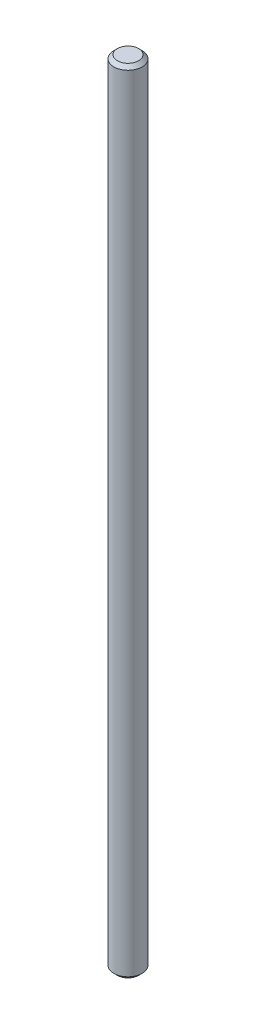
SolidWorks part; units mm, degrees
ref_plane "Front Plane" through (0, 0, 0) normal (0, 0, 1) x (1, 0, 0)
ref_plane "Top Plane" through (0, 0, 0) normal (0, 1, 0) x (1, 0, 0)
ref_plane "Right Plane" through (0, 0, 0) normal (1, 0, 0) x (0, 0, -1)
ref_plane "Plane1" through (0, 224, 0) normal (0, 1, 0) x (1, 0, 0)
sketch "Sketch1" plane through (0, 224, 0) normal (0, 1, 0) x (1, 0, 0)
  circle A0 centre (0, 0) radius 4
extrude "Boss-Extrude1" add sketch "Sketch1" against normal blind 224
chamfer "Chamfer1" distance 1 angle 45 2 edges at (0, 0, -4) (0, 224, -4)
